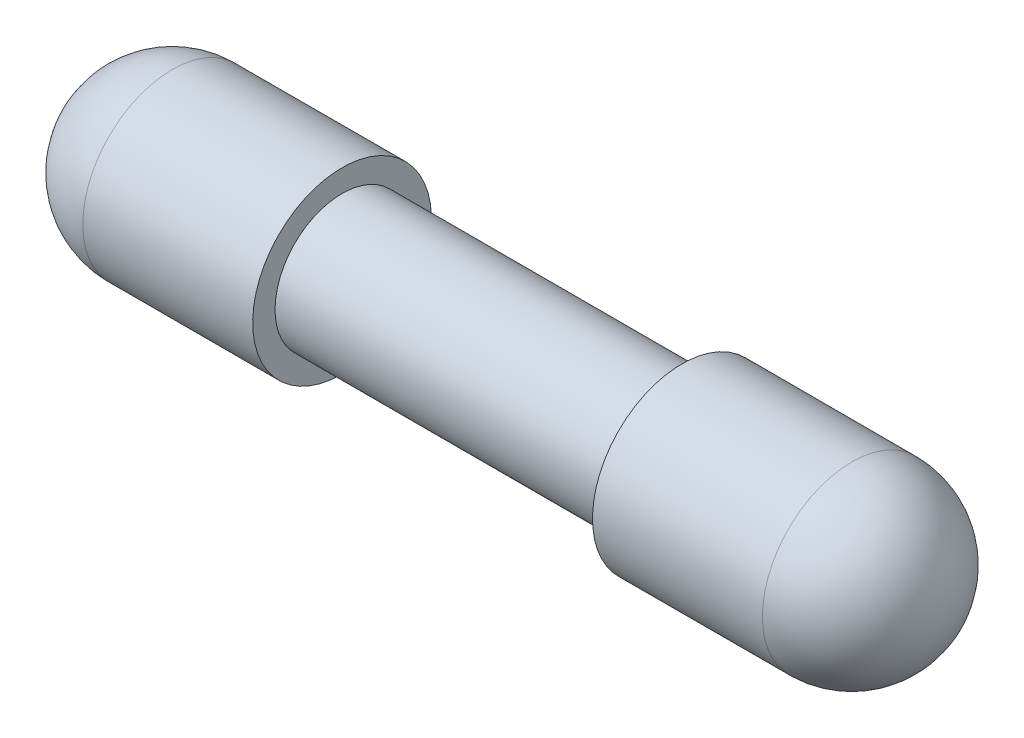
SolidWorks part; units mm, degrees
ref_plane "Front Plane" through (0, 0, 0) normal (0, 0, 1) x (1, 0, 0)
ref_plane "Top Plane" through (0, 0, 0) normal (0, 1, 0) x (1, 0, 0)
ref_plane "Right Plane" through (0, 0, 0) normal (1, 0, 0) x (0, 0, -1)
sketch "Sketch1" plane through (0, 0, 0) normal (0, 0, 1) x (1, 0, 0)
  line L0 (-36.0084, 13.6635) -> (49963.9916, 13.6635) construction
  line L1 (-6.6397, 13.6635) -> (-36.8022, 13.6635)
  line L2 (-21.7209, -986.3365) -> (-21.7209, 49013.6635) construction
  line L3 (-36.8022, 13.6635) -> (-59.8209, 13.6635)
  line L4 (-6.6397, 13.6635) -> (16.3791, 13.6635)
  line L5 (-51.8834, 21.601) -> (-36.8022, 21.601)
  line L6 (-36.8022, 21.601) -> (-36.8022, 19.6166)
  line L7 (-36.8022, 19.6166) -> (-6.6397, 19.6166)
  line L8 (8.4416, 21.601) -> (-6.6397, 21.601)
  line L9 (-18.5459, 13.6635) -> (-18.5459, 19.9857) construction
  line L10 (-24.8959, 19.9857) -> (-24.8959, 13.6635) construction
  line L11 (-6.6397, 21.601) -> (-6.6397, 19.6166)
  arc A0 (-51.8834, 21.601) -> (-59.8209, 13.6635) centre (-51.8834, 13.6635) ccw
  arc A1 (8.4416, 21.601) -> (16.3791, 13.6635) centre (8.4416, 13.6635) cw
  point P10 (-21.7209, 13.6635)
  point P25 (-21.7209, 19.6166)
  dimension "D3" = 15.875
  dimension "D1" = 0.7937
  dimension "D2" = 76.2
  dimension "D4" = 11.9062
revolve "Revolve1" add sketch "Sketch1" angle 360 about L4
